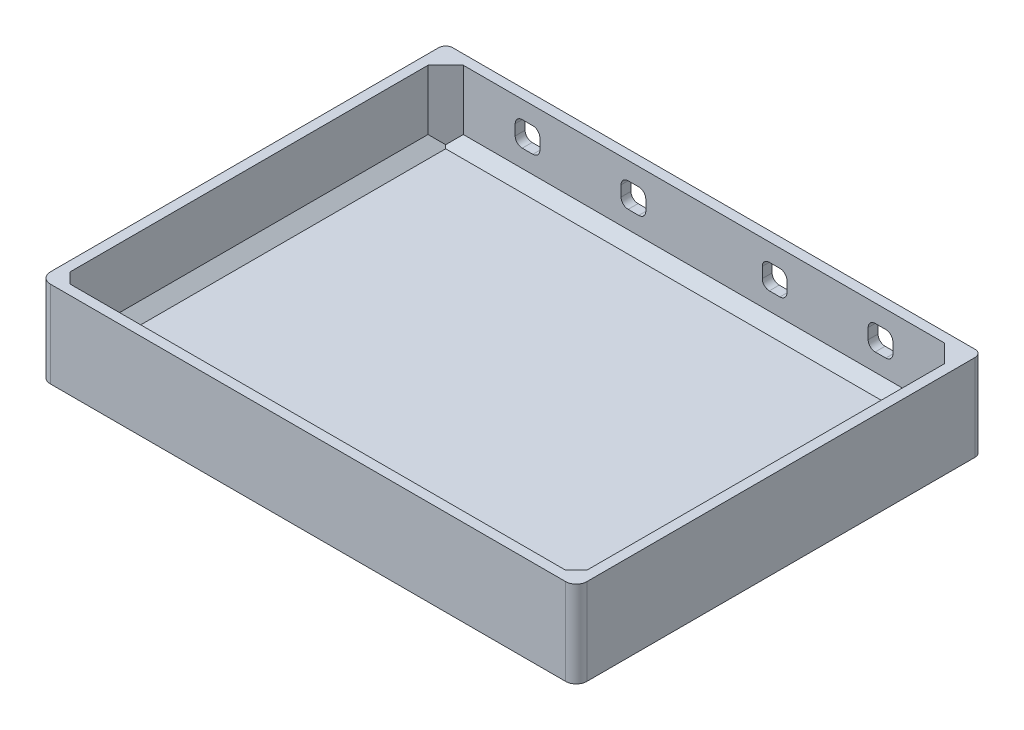
SolidWorks part; units mm, degrees
ref_plane "Plano frontal" through (0, 0, 0) normal (0, 0, 1) x (1, 0, 0)
ref_plane "Plano superior" through (0, 0, 0) normal (0, 1, 0) x (1, 0, 0)
ref_plane "Plano direito" through (0, 0, 0) normal (1, 0, 0) x (0, 0, -1)
sketch "Esboço2" plane through (0, 0, 0) normal (0, 1, 0) x (1, 0, 0)
  line L1 (-76, 57.5) -> (76, 57.5)
  line L2 (-76, 57.5) -> (-76, -57.5)
  line L3 (-76, -57.5) -> (76, -57.5)
  line L4 (76, 57.5) -> (76, -57.5)
  line L5 (-76, 57.5) -> (76, -57.5) construction
  line L6 (-76, -57.5) -> (76, 57.5) construction
  point P0 (0, 0)
  dimension "D1" = 152
  dimension "D2" = 115
extrude "Base" add sketch "Esboço2" along normal blind 4.5
sketch "Esboço3" plane through (0, 4.5, 0) normal (0, 1, 0) x (1, 0, 0)
  line L0 (-73.2, 54.7) -> (-73.2, -54.7)
  line L1 (-76, 57.5) -> (76, 57.5)
  line L2 (-76, 57.5) -> (-76, -57.5)
  line L3 (-76, -57.5) -> (76, -57.5)
  line L4 (76, 57.5) -> (76, -57.5)
  line L5 (-73.2, -54.7) -> (73.2, -54.7)
  line L6 (73.2, 54.7) -> (73.2, -54.7)
  line L7 (-73.2, 54.7) -> (73.2, 54.7)
  dimension "D1" = 2.8
extrude "Paredes" add sketch "Esboço3" along normal blind 20
chamfer "Chanfro da Base" distance 3 angle 45 4 edges at (0, 4.5, 54.7) (73.2, 4.5, 0) (-73.2, 4.5, 0) (0, 4.5, -54.7)
fillet "Filete7" radius 3 1 edges at (-76, 12.25, 57.5)
fillet "Filete8" radius 3 1 edges at (76, 12.25, 57.5)
fillet "Filete10" radius 2 1 edges at (-76, 12.25, -57.5)
fillet "Filete12" radius 2 1 edges at (76, 12.25, -57.5)
chamfer "Chanfro8" distance 3 angle 45 1 edges at (-73.2, 16, 54.7)
chamfer "Chanfro9" distance 3 angle 45 1 edges at (73.2, 16, 54.7)
chamfer "Chanfro14" distance 5 angle 45 1 edges at (-73.2, 16, -54.7)
chamfer "Chanfro17" distance 5 angle 45 1 edges at (73.2, 16, -54.7)
sketch "Esboço6" plane through (0, 0, -57.5) normal (0, 0, -1) x (-1, 0, 0)
  line L0 (0, 29.7797) -> (0, -7.5295) construction
  line L1 (-77.5508, 16) -> (86.6586, 16) construction
  line L2 (-74, 0) -> (74, 0) construction
  line L3 (16.5, 17.5) -> (16.5, 14.5)
  line L4 (-21.5, 19.5) -> (-18.5, 19.5)
  line L5 (-23.5, 17.5) -> (-23.5, 14.5)
  line L6 (-21.5, 12.5) -> (-18.5, 12.5)
  line L7 (-16.5, 17.5) -> (-16.5, 14.5)
  line L8 (-23.5, 19.5) -> (-16.5, 12.5) construction
  line L9 (-23.5, 12.5) -> (-16.5, 19.5) construction
  line L10 (21.5, 12.5) -> (18.5, 12.5)
  line L11 (23.5, 17.5) -> (23.5, 14.5)
  line L12 (21.5, 19.5) -> (18.5, 19.5)
  line L13 (46.5, 17.5) -> (46.5, 14.5)
  line L14 (-51.5, 19.5) -> (-48.5, 19.5)
  line L15 (-53.5, 17.5) -> (-53.5, 14.5)
  line L16 (-51.5, 12.5) -> (-48.5, 12.5)
  line L17 (-46.5, 17.5) -> (-46.5, 14.5)
  line L18 (-53.5, 19.5) -> (-46.5, 12.5) construction
  line L19 (-53.5, 12.5) -> (-46.5, 19.5) construction
  line L20 (51.5, 12.5) -> (48.5, 12.5)
  line L21 (53.5, 17.5) -> (53.5, 14.5)
  line L22 (51.5, 19.5) -> (48.5, 19.5)
  arc A0 (-16.5, 17.5) -> (-18.5, 19.5) centre (-18.5, 17.5) ccw
  arc A1 (-16.5, 14.5) -> (-18.5, 12.5) centre (-18.5, 14.5) cw
  arc A2 (-21.5, 12.5) -> (-23.5, 14.5) centre (-21.5, 14.5) cw
  arc A3 (-23.5, 17.5) -> (-21.5, 19.5) centre (-21.5, 17.5) cw
  arc A4 (16.5, 14.5) -> (18.5, 12.5) centre (18.5, 14.5) ccw
  arc A5 (21.5, 12.5) -> (23.5, 14.5) centre (21.5, 14.5) ccw
  arc A6 (23.5, 17.5) -> (21.5, 19.5) centre (21.5, 17.5) ccw
  arc A7 (16.5, 17.5) -> (18.5, 19.5) centre (18.5, 17.5) cw
  arc A8 (-46.5, 17.5) -> (-48.5, 19.5) centre (-48.5, 17.5) ccw
  arc A9 (-46.5, 14.5) -> (-48.5, 12.5) centre (-48.5, 14.5) cw
  arc A10 (-51.5, 12.5) -> (-53.5, 14.5) centre (-51.5, 14.5) cw
  arc A11 (-53.5, 17.5) -> (-51.5, 19.5) centre (-51.5, 17.5) cw
  arc A12 (46.5, 17.5) -> (48.5, 19.5) centre (48.5, 17.5) cw
  arc A13 (46.5, 14.5) -> (48.5, 12.5) centre (48.5, 14.5) ccw
  arc A14 (51.5, 12.5) -> (53.5, 14.5) centre (51.5, 14.5) ccw
  arc A15 (53.5, 17.5) -> (51.5, 19.5) centre (51.5, 17.5) ccw
  point P7 (-20, 16)
  point P36 (-50, 16)
  dimension "D5" = 2
  dimension "D9" = 2
  dimension "D1" = 16
  dimension "D2" = 7
  dimension "D3" = 7
  dimension "D4" = 20
  dimension "D6" = 7
  dimension "D7" = 7
  dimension "D8" = 50
extrude "Corte-extrusão4" cut sketch "Esboço6" against normal blind 10
